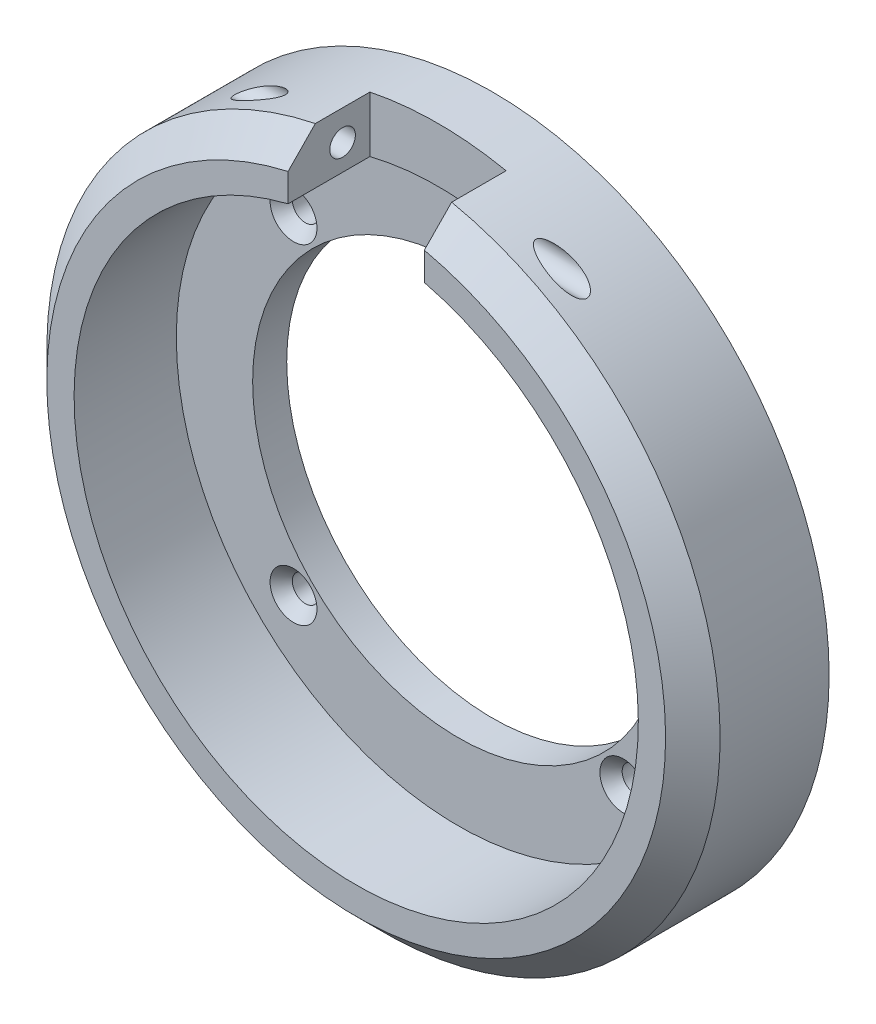
SolidWorks part; units mm, degrees
material "Chrome Stainless Steel"
ref_plane "Front Plane" through (0, 0, 0) normal (0, 0, 1) x (1, 0, 0)
ref_plane "Top Plane" through (0, 0, 0) normal (0, 1, 0) x (1, 0, 0)
ref_plane "Right Plane" through (0, 0, 0) normal (1, 0, 0) x (0, 0, -1)
sketch "Sketch1" plane through (0, 0, 0) normal (0, 0, 1) x (1, 0, 0)
  circle A0 centre (0, 0) radius 31.369
  dimension "D1" = 62.738
extrude "Boss-Extrude1" add sketch "Sketch1" along normal blind 12.7
sketch "Sketch2" plane through (0, 0, 0) normal (0, 0, -1) x (-1, 0, 0)
  circle A0 centre (0, 0) radius 19.177
  dimension "D1" = 38.354
extrude "Cut-Extrude1" cut sketch "Sketch2" against normal through all
sketch "Sketch3" plane through (0, 0, 12.7) normal (0, 0, 1) x (1, 0, 0)
  circle A0 centre (0, 0) radius 26.289
  circle A1 centre (0, 0) radius 31.369 construction
  point P3 (-31.369, 0)
  point P4 (-26.289, 0)
  dimension "D1" = 5.08
ref_plane "Plane1" through (0, 0, 3.175) normal (0, 0, -1) x (-1, 0, 0)
extrude "Cut-Extrude2" cut sketch "Sketch3" against normal up to surface (9.525 mm away)
chamfer "Chamfer1" distance 2.54 angle 45 1 edges at (31.369, 0, 12.7)
sketch "Sketch5" plane through (0, 0, 3.175) normal (0, 0, 1) x (1, 0, 0)
  line L1 (-15.367, 15.367) -> (15.367, 15.367)
  line L2 (-15.367, 15.367) -> (-15.367, -15.367)
  line L3 (-15.367, -15.367) -> (15.367, -15.367)
  line L4 (15.367, 15.367) -> (15.367, -15.367)
  line L5 (-15.367, 15.367) -> (15.367, -15.367) construction
  line L6 (-15.367, -15.367) -> (15.367, 15.367) construction
  point P0 (0, 0)
  dimension "D1" = 30.734
hole_wizard "CSK for #2 Flat Head Machine Screw (100)1" positions "Sketch7" profile "Sketch6" countersink size "#2" standard "ANSI Inch" end condition through all
sketch "Sketch7" plane through (0, 0, 3.175) normal (0, 0, 1) x (1, 0, 0)
  point P0 (-15.367, -15.367)
  point P3 (-15.367, 15.367)
  point P6 (15.367, 15.367)
  point P9 (15.367, -15.367)
sketch "Sketch6" plane through (-15.367, -15.367, 3.175) normal (1, 0, 0) x (0, -1, 0)
  line L0 (0, 0) -> (0, 3.175)
  line L1 (0, 3.175) -> (1.2192, 3.175)
  line L2 (1.2192, 3.175) -> (1.2192, 1.1103)
  line L3 (1.2192, 1.1103) -> (2.1844, 0)
  line L5 (2.1844, 0) -> (0, 0)
  line L6 (-1.2192, 1.1103) -> (-2.1844, 0) construction
  line L11 (0, -6.35) -> (0, 107.95) construction
  dimension "Thru Hole Dia." = 2.4384
  dimension "Thru Hole Depth" = 3.175
  dimension "Near C'Sink Dia." = 4.3688
  dimension "Near C'Sink Angle" = 82
sketch "Sketch9" plane through (0, 0, 0) normal (0, 0, -1) x (-1, 0, 0)
  line L0 (0, 0) -> (20.32, 20.32)
  line L1 (0, 0) -> (20.32, -20.32)
  line L2 (0, 0) -> (-20.32, -20.32)
  line L3 (0, 0) -> (-20.32, 20.32)
  circle A0 centre (20.32, 20.32) radius 1.27
  circle A1 centre (20.32, -20.32) radius 1.27
  circle A2 centre (-20.32, -20.32) radius 1.27
  circle A3 centre (-20.32, 20.32) radius 1.27
  point P13 (0, 0)
  dimension "D1" = 4
  dimension "D2" = 2.54
  dimension "D3" = 40.64
hole_wizard "#4-40 Tapped Hole1" positions "Sketch11" profile "Sketch10" tap size "#4-40" standard "ANSI Inch"
sketch "Sketch11" plane through (0, 0, 0) normal (0, 0, -1) x (-1, 0, 0)
  point P0 (-20.32, 20.32)
  point P3 (20.32, 20.32)
  point P6 (20.32, -20.32)
  point P9 (-20.32, -20.32)
sketch "Sketch10" plane through (20.32, 20.32, 0) normal (1, 0, 0) x (0, 1, 0)
  line L0 (0, 0) -> (0, 8.2738)
  line L1 (0, 8.2738) -> (1.1303, 7.5946)
  line L2 (1.1303, 7.5946) -> (1.1303, 0.4572)
  line L3 (1.1303, 0.4572) -> (1.5875, 0)
  line L5 (1.5875, 0) -> (0, 0)
  line L6 (-1.1303, 0.4572) -> (-1.5875, 0) construction
  line L10 (0, 8.2738) -> (-1.1303, 7.5946) construction
  line L11 (0, -6.35) -> (0, 107.95) construction
  dimension "Tap Drill Dia." = 2.2606
  dimension "Tap Drill Depth" = 7.5946
  dimension "Near C'Sink Dia." = 3.175
  dimension "Near C'Sink Angle" = 90
  dimension "Drill Angle" = 118
cosmetic thread "Hole Thread1" parameters "D1"=5.6896, "D2"=2.8448
cosmetic thread "Hole Thread2" parameters "D1"=5.6896, "D2"=2.8448
cosmetic thread "Hole Thread3" parameters "D1"=5.6896, "D2"=2.8448
cosmetic thread "Hole Thread4" parameters "D1"=5.6896, "D2"=2.8448
sketch "Sketch12" plane through (0, 0, 12.7) normal (0, 0, 1) x (1, 0, 0)
  line L0 (0, 0) -> (0, 31.369) construction
  line L1 (-6.35, 31.369) -> (6.35, 31.369)
  line L2 (6.35, 31.369) -> (6.35, 22.4236)
  line L3 (6.35, 22.4236) -> (-6.35, 22.4236)
  line L4 (-6.35, 31.369) -> (-6.35, 22.4236)
  circle A0 centre (0, 0) radius 31.369 construction
  point P10 (0, 22.4236)
  dimension "D1" = 12.7
extrude "Cut-Extrude3" cut sketch "Sketch12" against normal blind 7.62
sketch "Sketch13" plane through (-6.35, 0, 0) normal (1, 0, 0) x (0, 0, -1)
  line L0 (-5.08, 30.7196) -> (-10.16, 30.7196) construction
  line L1 (-5.08, 31.369) -> (-5.08, 30.7196) construction
  circle A0 centre (-7.62, 27.9256) radius 1.1938
  dimension "D1" = 2.3876
  dimension "D2" = 2.794
  dimension "D3" = 2.54
extrude "Cut-Extrude4" cut sketch "Sketch13" against normal through all and the other way through all
